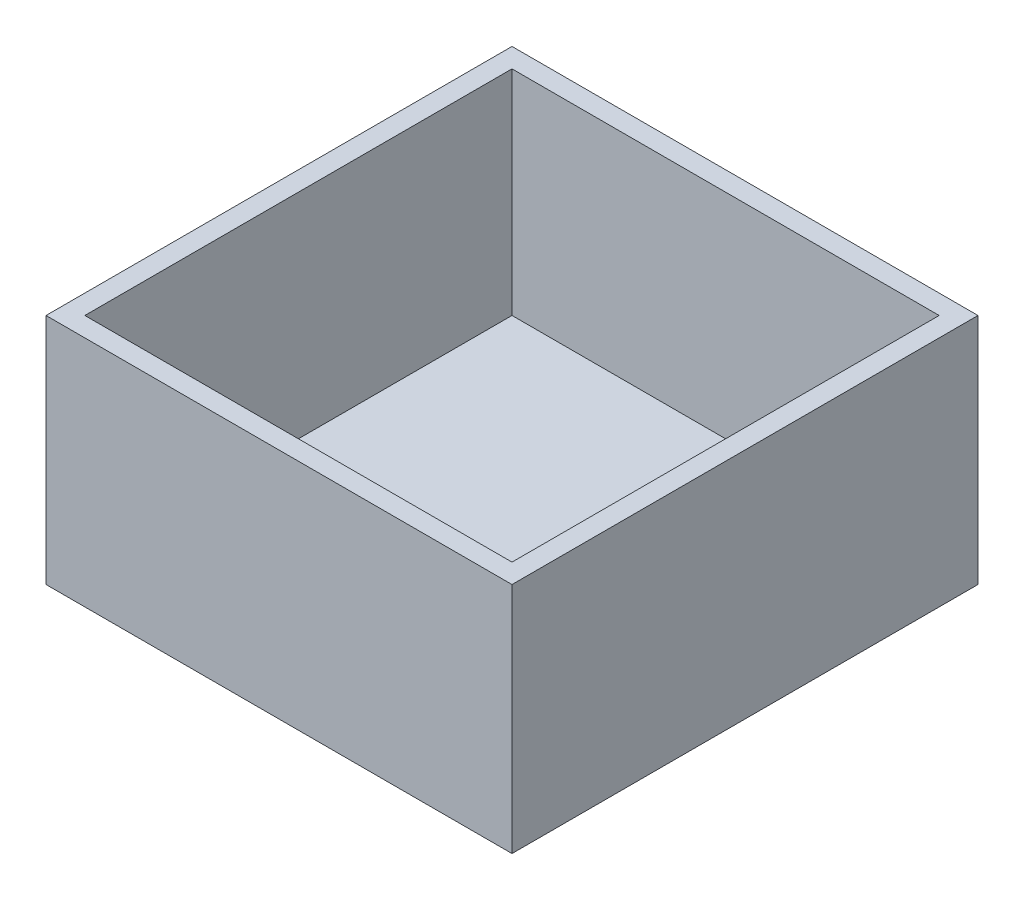
SolidWorks part; units mm, degrees
ref_plane "Front Plane" through (0, 0, 0) normal (0, 0, 1) x (1, 0, 0)
ref_plane "Top Plane" through (0, 0, 0) normal (0, 1, 0) x (1, 0, 0)
ref_plane "Right Plane" through (0, 0, 0) normal (1, 0, 0) x (0, 0, -1)
sketch "Sketch1" plane through (0, 0, 0) normal (0, 1, 0) x (1, 0, 0)
  line L1 (-60, -60) -> (60, -60)
  line L2 (-60, -60) -> (-60, 60)
  line L3 (-60, 60) -> (60, 60)
  line L4 (60, -60) -> (60, 60)
  line L5 (-60, -60) -> (60, 60) construction
  line L6 (-60, 60) -> (60, -60) construction
  point P0 (0, 0)
  dimension "D1" = 120
  dimension "D2" = 120
extrude "Boss-Extrude1" add sketch "Sketch1" along normal blind 5
sketch "Sketch2" plane through (0, 5, 0) normal (0, 1, 0) x (1, 0, 0)
  line L1 (-60, -60) -> (60, -60)
  line L2 (-60, -60) -> (-60, 60)
  line L3 (-60, 60) -> (60, 60)
  line L4 (60, -60) -> (60, 60)
  line L5 (-60, -60) -> (60, 60) construction
  line L6 (-60, 60) -> (60, -60) construction
  line L7 (-55, -55) -> (55, -55)
  line L8 (-55, -55) -> (-55, 55)
  line L9 (-55, 55) -> (55, 55)
  line L10 (55, -55) -> (55, 55)
  line L11 (-55, -55) -> (55, 55) construction
  line L12 (-55, 55) -> (55, -55) construction
  point P0 (0, 0)
  point P7 (0, 0)
  dimension "D1" = 110
  dimension "D2" = 110
extrude "Boss-Extrude2" add sketch "Sketch2" along normal blind 55
